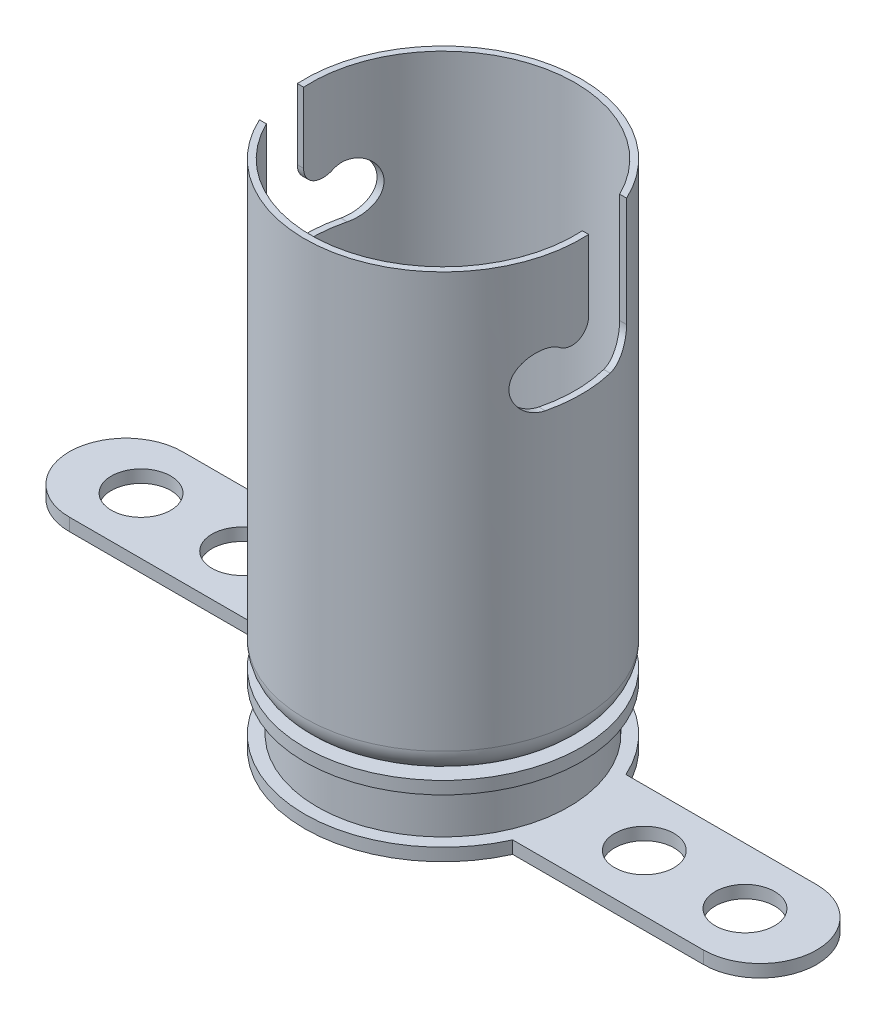
SolidWorks part; units mm, degrees
ref_plane "Front Plane" through (0, 0, 0) normal (0, 0, 1) x (1, 0, 0)
ref_plane "Top Plane" through (0, 0, 0) normal (0, 1, 0) x (1, 0, 0)
ref_plane "Right Plane" through (0, 0, 0) normal (1, 0, 0) x (0, 0, -1)
sketch "Sketch1" plane through (0, 0, 0) normal (0, 0, 1) x (1, 0, 0)
  line L0 (-5.6397, 32.4008) -> (5.5603, 32.4008) construction
  line L2 (0, -2.4) -> (0, 20.3) construction
  line L3 (0, 20.3) -> (5.5, 20.3) construction
  line L4 (5.5, 20.3) -> (5.5, 3.8)
  line L5 (4.5, 2.8) -> (5.5, 2.8)
  line L6 (5.5, 2.8) -> (5.5, 2.3)
  line L7 (5.5, 2.3) -> (5, 2.3)
  line L8 (5, 2.3) -> (5, 0.5)
  line L9 (5, 0.5) -> (5.5, 0.5)
  line L10 (5.5, 0.5) -> (5.5, 0)
  line L11 (5.5, 0) -> (0, 0)
  line L12 (5.5, 20.3) -> (5.25, 20.3)
  line L13 (5.25, 20.3) -> (5.25, 3.8)
  line L14 (4.5, 3.05) -> (0, 3.05)
  line L15 (4.5, 3.05) -> (4.5, 2.8) construction
  line L16 (0, 3.05) -> (0, 0)
  arc A0 (5.5, 3.8) -> (4.5, 2.8) centre (4.5, 3.8) cw
  arc A1 (5.25, 3.8) -> (4.5, 3.05) centre (4.5, 3.8) cw
  point P2 (0, -1.7154)
  dimension "D1" = 11.2
  dimension "D2" = 22.7
  dimension "D4" = 0.5
  dimension "D5" = 11
  dimension "D6" = 1
  dimension "D7" = 10
  dimension "D8" = 1.8
  dimension "D9" = 17.5
  dimension "D10" = 0.25
  dimension "D11" = 0.25
revolve "Revolve1" add sketch "Sketch1" angle 360 about L2
sketch "Sketch2" plane through (0, 0, 0) normal (0, -1, 0) x (1, 0, 0)
  line L0 (5.0187, 2.25) -> (12.6, 2.25)
  line L1 (14.85, 0) -> (0, 0) construction
  line L2 (0, 0) -> (0, 5.5) construction
  line L3 (5.0187, -2.25) -> (12.6, -2.25)
  circle A0 centre (0, 0) radius 5.5 construction
  arc A1 (12.6, 2.25) -> (12.6, -2.25) centre (12.6, 0) cw
  circle A2 centre (12, 0) radius 1.18
  circle A3 centre (8, 0) radius 1.18
  arc A4 (5.0187, -2.25) -> (5.0187, 2.25) centre (0, 0) ccw
  arc A5 (0, 5.5) -> (5.0187, -2.25) centre (0, 0) ccw construction
  arc A6 (5.0187, 2.25) -> (0, 5.5) centre (0, 0) ccw construction
  point P7 (12.3907, 0)
  dimension "D3" = 2.36
  dimension "D1" = 29.7
  dimension "D2" = 4.5
  dimension "D4" = 16
  dimension "D5" = 24
extrude "Boss-Extrude1" add sketch "Sketch2" against normal up to surface (0.5 mm away) up to face at (0, 0.5, -5)
sketch "Sketch3" plane through (0, 2.3, 0) normal (0, -1, 0) x (1, 0, 0)
  line L0 (-5.0187, 2.25) -> (-12.6, 2.25)
  line L1 (-14.85, 0) -> (0, 0) construction
  line L2 (0, 0) -> (0, 5.5) construction
  line L3 (-5.0187, -2.25) -> (-12.6, -2.25)
  circle A2 centre (-12, 0) radius 1.18
  circle A3 centre (-8, 0) radius 1.18
  arc A4 (-5.0187, -2.25) -> (-5.0187, 2.25) centre (0, 0) ccw construction
  arc A5 (0, 5.5) -> (-5.0187, 2.25) centre (0, 0) ccw construction
  arc A6 (-5.0187, 2.25) -> (-5.5, 0) centre (0, 0) ccw
  circle A8 centre (0, 0) radius 5.5 construction
  arc A9 (-12.6, 2.25) -> (-12.6, -2.25) centre (-12.6, 0) ccw
  arc A10 (-12.6, -2.25) -> (-10.35, 0) centre (-12.6, 0) ccw construction
  arc A11 (-10.35, 0) -> (-12.6, 2.25) centre (-12.6, 0) ccw construction
  arc A12 (-5.5, 0) -> (-5.0187, -2.25) centre (0, 0) ccw
  arc A13 (-5.0187, 2.25) -> (-5.5, 0) centre (0, 0) ccw construction
  arc A14 (-5.0187, -2.25) -> (0, 5.5) centre (0, 0) ccw construction
  arc A15 (-5.5, 0) -> (-5.0187, -2.25) centre (0, 0) ccw construction
  point P3 (0, 0)
  point P4 (0, 0)
  point P7 (0, 0)
  point P8 (-17.7976, 0)
  point P13 (-18.3809, 0)
  dimension "D3" = 2.36
  dimension "D1" = 29.7
  dimension "D2" = 4.5
  dimension "D4" = 24
  dimension "D5" = 16
extrude "Boss-Extrude2" add sketch "Sketch3" against normal up to surface (0.5 mm away) up to face at (0, 2.8, -4.5)
sketch "Sketch4" plane through (0, 0, 0) normal (1, 0, 0) x (0, 0, -1)
  line L0 (-5.6758, 23.6196) -> (5.5242, 23.6196) construction
  line L1 (2.2988, 20.3) -> (2.2988, 15.95)
  line L2 (5.25, 20.3) -> (-5.25, 20.3) construction
  line L3 (1.2988, 14.95) -> (-1.2836, 14.95)
  line L4 (0.2988, 17.5063) -> (0.2988, 20.3)
  line L5 (5.5, 20.3) -> (-5.5, 20.3) construction
  line L6 (-2.3512, 16.0176) -> (2.2988, 16.0176) construction
  line L7 (2.2988, 20.3) -> (0.2988, 20.3)
  arc A0 (2.2988, 15.95) -> (1.2988, 14.95) centre (1.2988, 15.95) cw
  arc A1 (-1.2836, 14.95) -> (-1.2836, 17.0851) centre (-1.2836, 16.0176) cw
  arc A2 (-1.2836, 17.0851) -> (-0.8063, 16.9336) centre (-1.2836, 16.2573) cw
  arc A3 (-0.8063, 16.9336) -> (0.2988, 17.5063) centre (-0.4021, 17.5063) ccw
  dimension "D5" = 1
  dimension "D8" = 1.0676
  dimension "D9" = 0.8278
  dimension "D1" = 11.2
  dimension "D2" = 2.2988
  dimension "D3" = 2
  dimension "D4" = 5.35
  dimension "D6" = 4.65
  dimension "D7" = 2.7937
extrude "Cut-Extrude1" cut sketch "Sketch4" along normal blind 10
ref_axis "Axis1" through (0, 20.3, 0) along (0, -1, 0)
pattern_circular "CirPattern1" count 2 over 180 about axis through (0, 20.3, 0) along (0, -1, 0) of "Cut-Extrude1"
